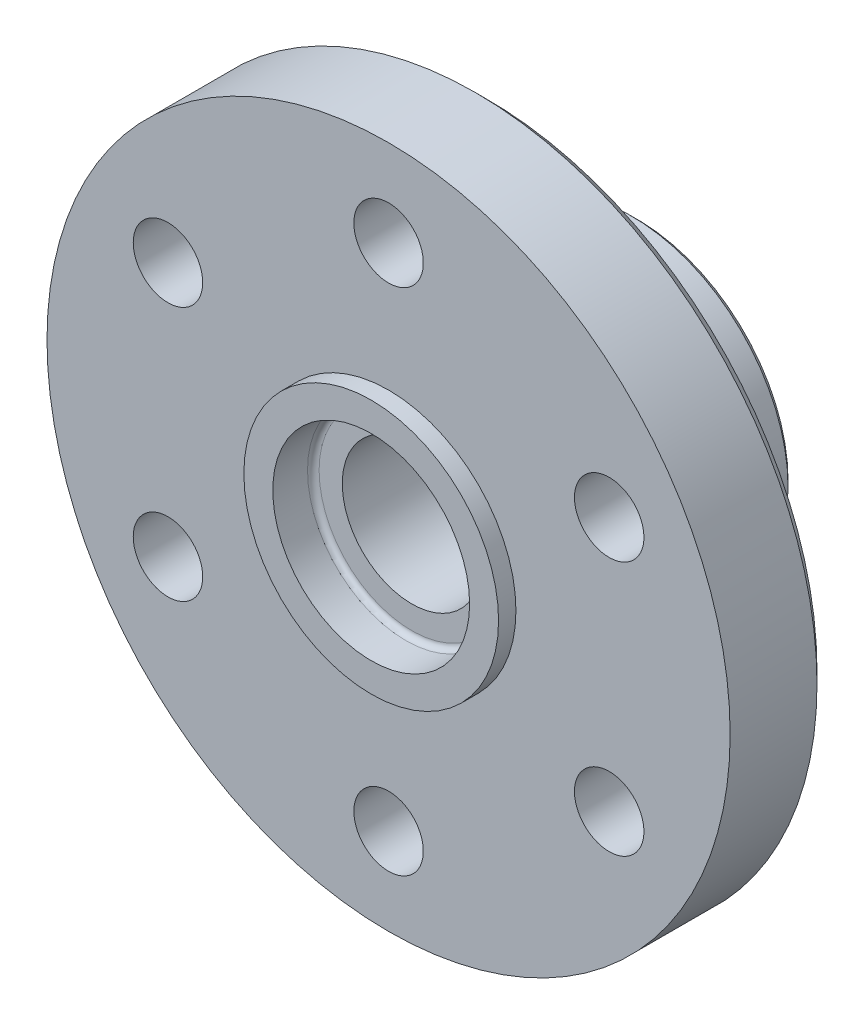
SolidWorks part; units mm, degrees
ref_plane "Front Plane" through (0, 0, 0) normal (0, 0, 1) x (1, 0, 0)
ref_plane "Top Plane" through (0, 0, 0) normal (0, 1, 0) x (1, 0, 0)
ref_plane "Right Plane" through (0, 0, 0) normal (1, 0, 0) x (0, 0, -1)
sketch "Sketch1" plane through (0, 0, 0) normal (1, 0, 0) x (0, 0, -1)
  line L0 (-9.0012, 0) -> (24.6865, 0) construction
  line L3 (-11.2089, 22) -> (-11.2089, 59)
  line L4 (-11.2089, 59) -> (5.7911, 59)
  line L5 (5.7911, 59) -> (5.7911, 27)
  line L6 (5.7911, 27) -> (31.7911, 27)
  line L7 (31.7911, 27) -> (31.7911, 12)
  line L9 (-7.2089, 12) -> (31.7911, 12)
  line L10 (-11.2089, 22) -> (-14.2089, 22)
  line L11 (-14.2089, 22) -> (-14.2089, 17)
  line L12 (-14.2089, 17) -> (-7.2089, 17)
  line L13 (-7.2089, 17) -> (-7.2089, 12)
  dimension "D1" = 44
  dimension "D2" = 118
  dimension "D3" = 54
  dimension "D4" = 34
  dimension "D5" = 24
  dimension "D6" = 17
  dimension "D7" = 43
  dimension "D8" = 3
  dimension "D9" = 4
revolve "Revolve1" add sketch "Sketch1" angle 360 about L0
sketch "Sketch2" plane through (0, 0, -5.7911) normal (0, 0, -1) x (-1, 0, 0)
  circle A0 centre (0, 44) radius 6
  dimension "D1" = 12
  dimension "D2" = 44
extrude "Cut-Extrude1" cut sketch "Sketch2" against normal up to next
pattern_circular "CirPattern1" count 6 over 360 about axis through (0, 0, 0) along (0, 0, 1) of "Cut-Extrude1"
fillet "Fillet1" radius 2 1 edges at (27, 0, -5.7911)
fillet "Fillet2" radius 1 1 edges at (17, 0, 7.2089)
chamfer "Chamfer1" distance 1 angle 45 2 edges at (12, 0, -31.7911) (27, 0, -31.7911)
chamfer "Chamfer2" distance 2 angle 45 1 edges at (59, 0, -5.7911)
